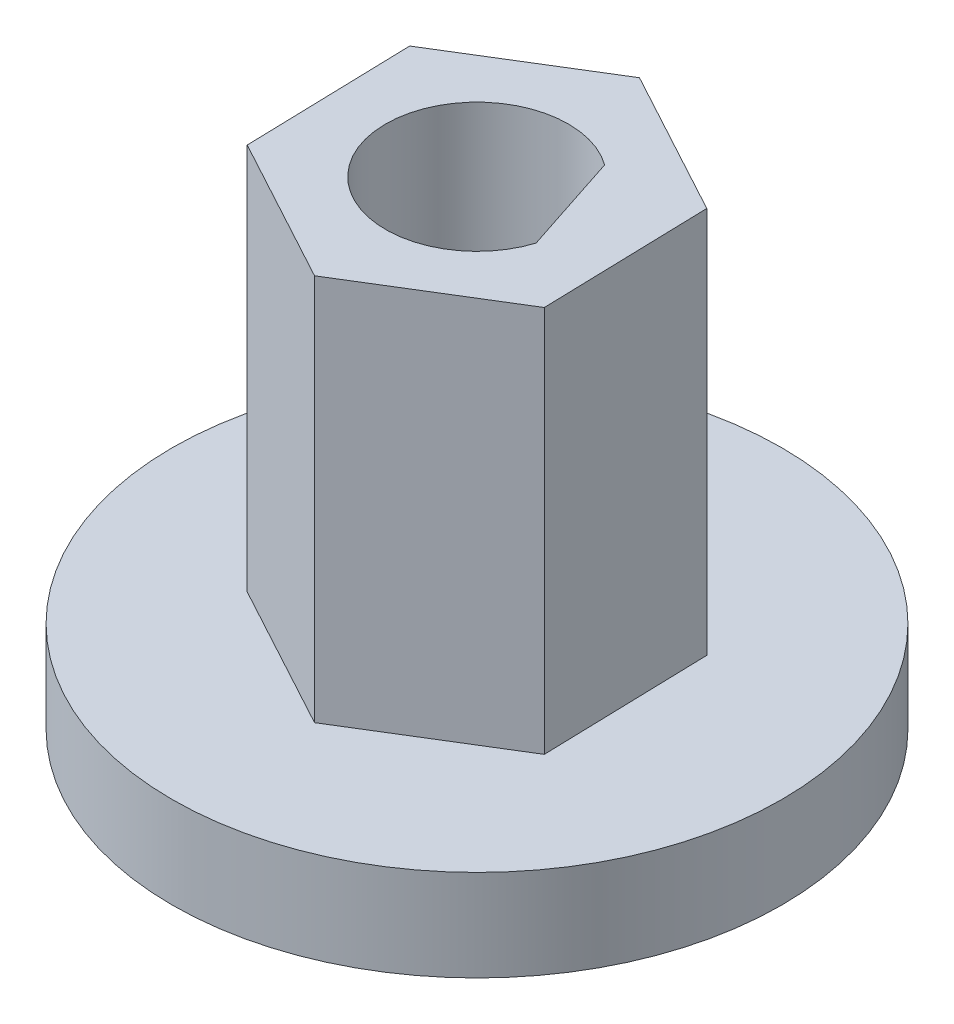
SolidWorks part; units mm, degrees
ref_plane "Front" through (0, 0, 0) normal (0, 0, 1) x (1, 0, 0)
ref_plane "Top" through (0, 0, 0) normal (0, 1, 0) x (1, 0, 0)
ref_plane "Right" through (0, 0, 0) normal (1, 0, 0) x (0, 0, -1)
sketch "Sketch1" plane through (0, 0, 0) normal (0, 1, 0) x (1, 0, 0)
  circle A0 centre (0, 0) radius 10
extrude "Boss-Extrude1" add sketch "Sketch1" along normal blind 3
sketch "Sketch2" plane through (0, 3, 0) normal (0, 1, 0) x (1, 0, 0)
  line L1 (0.1489, -5.48) -> (4.8203, -2.6111)
  line L2 (4.8203, -2.6111) -> (4.6714, 2.8689)
  line L3 (4.6714, 2.8689) -> (-0.1489, 5.48)
  line L4 (-0.1489, 5.48) -> (-4.8203, 2.6111)
  line L5 (-4.8203, 2.6111) -> (-4.6714, -2.8689)
  line L6 (-4.6714, -2.8689) -> (0.1489, -5.48)
  circle A0 centre (0, 0) radius 4.7476 construction
  dimension "D1" = 5.48
extrude "Boss-Extrude2" add sketch "Sketch2" along normal blind 12.7
sketch "Sketch6" plane through (0, 15.7, 0) normal (0, 1, 0) x (1, 0, 0)
  line L0 (1.758, 2.431) -> (2.8558, -0.919)
  circle A0 centre (0, 0) radius 3
  dimension "D1" = 3.35
extrude "Cut-Extrude1" cut sketch "Sketch6" against normal blind 23 contours L0 A0
